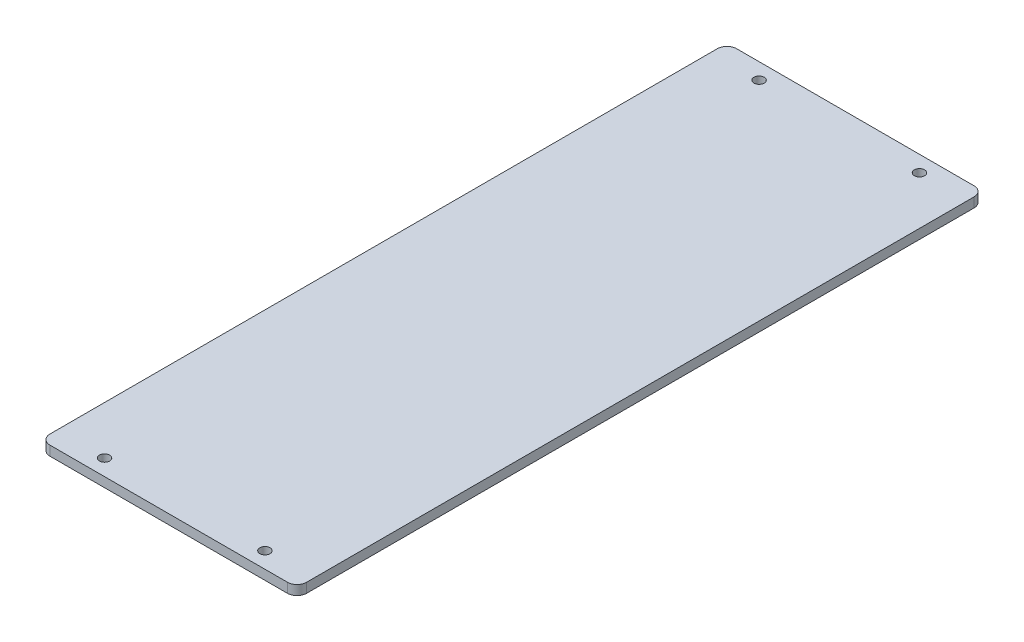
SolidWorks part; units mm, degrees
material "PET"
ref_plane "Front Plane" through (0, 0, 0) normal (0, 0, 1) x (1, 0, 0)
ref_plane "Top Plane" through (0, 0, 0) normal (0, 1, 0) x (1, 0, 0)
ref_plane "Right Plane" through (0, 0, 0) normal (1, 0, 0) x (0, 0, -1)
sketch "Sketch1" plane through (0, 0, 0) normal (0, 1, 0) x (1, 0, 0)
  line L1 (-37, 107) -> (37, 107)
  line L2 (-40, 104) -> (-40, -104)
  line L3 (-37, -107) -> (37, -107)
  line L4 (40, 104) -> (40, -104)
  line L5 (-40, 107) -> (40, -107) construction
  line L6 (-40, -107) -> (40, 107) construction
  arc A0 (37, -107) -> (40, -104) centre (37, -104) ccw
  arc A1 (-40, -104) -> (-37, -107) centre (-37, -104) ccw
  arc A2 (37, 107) -> (40, 104) centre (37, 104) cw
  arc A3 (-37, 107) -> (-40, 104) centre (-37, 104) ccw
  point P0 (0, 0)
  dimension "D3" = 3
  dimension "D1" = 80
  dimension "D2" = 214
extrude "Spine_Body" add sketch "Sketch1" along normal mid plane 3
sketch "Sketch2" plane through (0, 1.5, 0) normal (0, 1, 0) x (1, 0, 0)
  line L0 (0, 0) -> (9.8089, 0) construction
  circle A2 centre (-25, -102) radius 1.6
  circle A3 centre (25, -102) radius 1.6
  circle A4 centre (25, 102) radius 1.6
  circle A5 centre (-25, 102) radius 1.6
  dimension "D1" = 3.2
  dimension "D4" = 3.2
  dimension "D5" = 102
  dimension "D7" = 25
  dimension "D8" = 25
extrude "Tab_Holes" cut sketch "Sketch2" against normal through all
equation "\"Sp_L\"= 214mm"
equation "\"Sp_W\"= 80mm"
equation "\"Sp_T\"= 3mm"
equation "\"D2@Sketch1\"=\"Sp_L\""
equation "\"D1@Sketch1\"=\"Sp_W\""
equation "\"D1@Spine_Body\"=\"Sp_T\""
